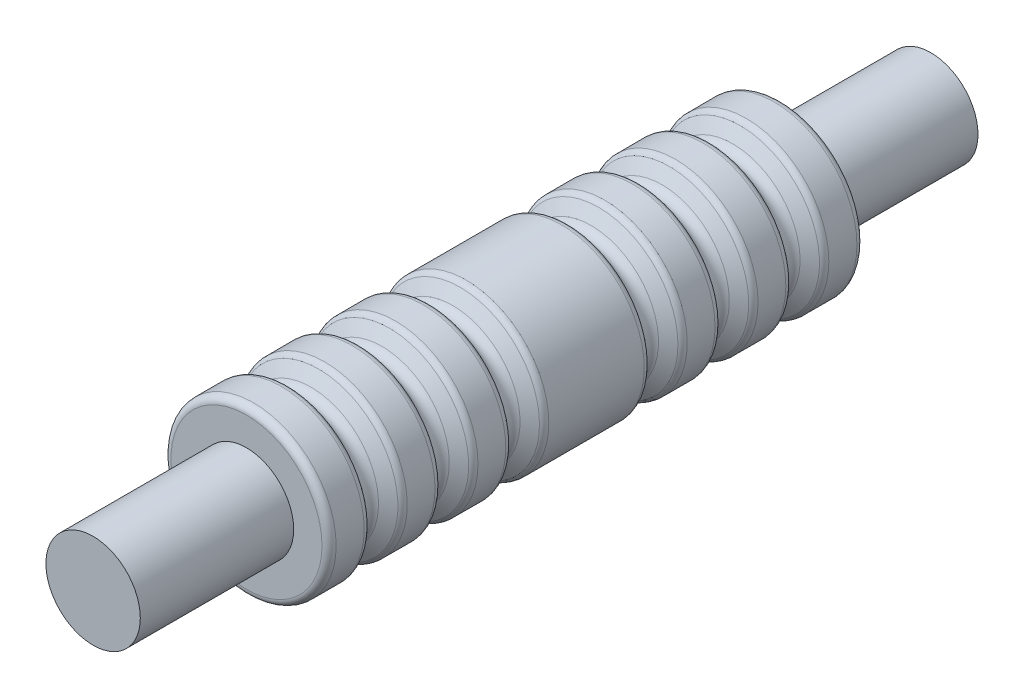
SolidWorks part; units mm, degrees
ref_plane "Спереди" through (0, 0, 0) normal (0, 0, 1) x (1, 0, 0)
ref_plane "Сверху" through (0, 0, 0) normal (0, 1, 0) x (1, 0, 0)
ref_plane "Справа" through (0, 0, 0) normal (1, 0, 0) x (0, 0, -1)
sketch "Эскиз1" plane through (0, 0, 0) normal (0, 0, 1) x (1, 0, 0)
  circle A0 centre (0, 0) radius 2
extrude "Вытянуть1" add sketch "Эскиз1" against normal blind 35.5
ref_plane "Плоскость1" through (0, 0, -6.5) normal (0, 0, 1) x (1, 0, 0)
sketch "Эскиз2" plane through (0, 0, -6.5) normal (0, 0, 1) x (1, 0, 0)
  circle A0 centre (0, 0) radius 3.5
extrude "Вытянуть2" add sketch "Эскиз2" against normal blind 22.67
sketch "Эскиз3" plane through (0, 0, 0) normal (1, 0, 0) x (0, 0, -1)
  line L0 (8.9001, 8.2418) -> (8.9001, 5.8071) construction
  line L1 (12.6725, 3.5431) -> (12.2386, 2.8538)
  line L2 (10.4001, 6.675) -> (10.4001, 4.9932) construction
  line L3 (9.6725, 3.5431) -> (8.1277, 3.5431)
  line L5 (8.1277, 3.5431) -> (8.5616, 2.8538)
  line L6 (9.6725, 3.5431) -> (9.2386, 2.8538)
  line L7 (11.1277, 3.5431) -> (11.5616, 2.8538)
  line L8 (17.8339, -11) -> (17.8339, 11.4105) construction
  line L9 (11.1277, 3.5431) -> (12.6725, 3.5431)
  line L10 (6.5, 0) -> (-0.5066, 0) construction
  line L12 (15.6454, 3.5) -> (15.2386, 2.8538)
  line L13 (14.1548, 3.5) -> (14.5616, 2.8538)
  line L14 (15.6454, 3.5) -> (14.1548, 3.5)
  line L15 (21.5129, 3.5) -> (21.1062, 2.8538)
  line L16 (20.0224, 3.5) -> (20.4291, 2.8538)
  line L17 (20.0224, 3.5) -> (21.5129, 3.5)
  line L18 (22.9953, 3.5431) -> (23.4291, 2.8538)
  line L19 (24.54, 3.5431) -> (24.1062, 2.8538)
  line L20 (24.54, 3.5431) -> (22.9953, 3.5431)
  line L21 (27.54, 3.5431) -> (27.1062, 2.8538)
  line L22 (25.9953, 3.5431) -> (26.4291, 2.8538)
  line L23 (25.9953, 3.5431) -> (27.54, 3.5431)
  arc A0 (9.2386, 2.8538) -> (8.5616, 2.8538) centre (8.9001, 3.0668) cw
  arc A1 (11.5616, 2.8538) -> (12.2386, 2.8538) centre (11.9001, 3.0668) ccw
  arc A2 (15.2386, 2.8538) -> (14.5616, 2.8538) centre (14.9001, 3.0668) cw
  arc A3 (20.4291, 2.8538) -> (21.1062, 2.8538) centre (20.7676, 3.0668) ccw
  arc A4 (24.1062, 2.8538) -> (23.4291, 2.8538) centre (23.7676, 3.0668) cw
  arc A5 (26.4291, 2.8538) -> (27.1062, 2.8538) centre (26.7676, 3.0668) ccw
  point P12 (8.9001, 2.3159)
  dimension "D2" = 0.4
revolve "Вырез-Повернуть1" cut sketch "Эскиз3" angle 360 about L10
fillet "Скругление1" radius 0.3 12 edges at (-3.5, 0, -27.5129) (3.5, 0, -26.0224) (-3.5, 0, -24.5129) (3.5, 0, -23.0224) (-3.5, 0, -21.5129) (-3.5, 0, -20.0224) (-3.5, 0, -15.6454) (-3.5, 0, -14.1548) (-3.5, 0, -12.6454) (3.5, 0, -11.1548) (-3.5, 0, -9.6454) (3.5, 0, -8.1548)
fillet "Скругление2" radius 0.3 2 edges at (3.5, 0, -29.17) (3.5, 0, -6.5)
